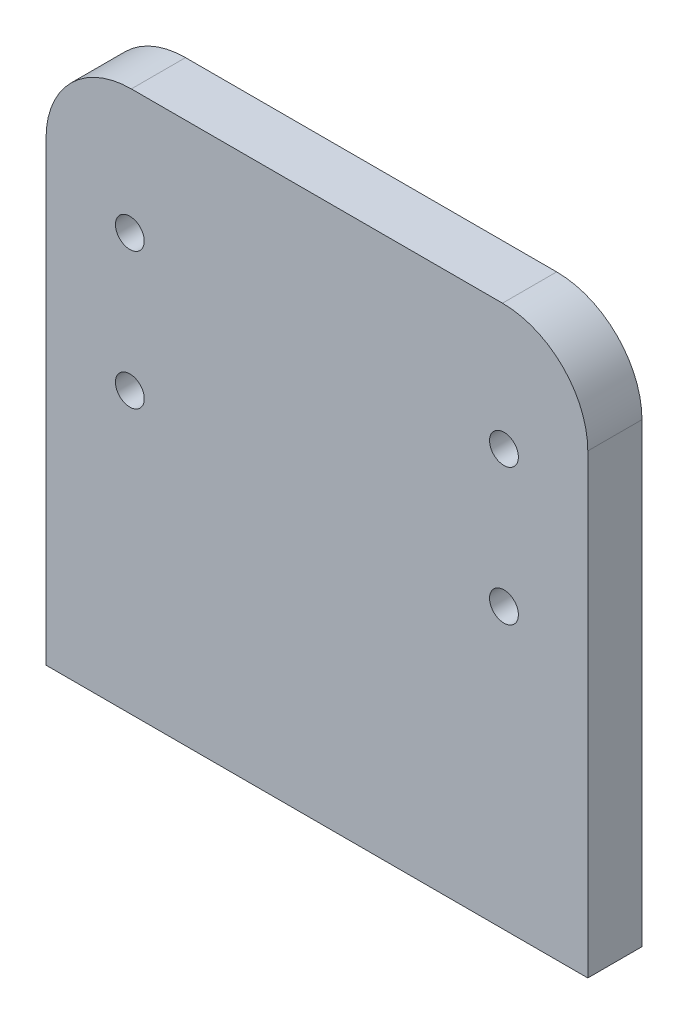
SolidWorks part; units mm, degrees
ref_plane "Alzado" through (0, 0, 0) normal (0, 0, 1) x (1, 0, 0)
ref_plane "Planta" through (0, 0, 0) normal (0, 1, 0) x (1, 0, 0)
ref_plane "Vista lateral" through (0, 0, 0) normal (1, 0, 0) x (0, 0, -1)
sketch "Croquis1" plane through (0, 0, 0) normal (0, 0, 1) x (1, 0, 0)
  line L1 (43.5, 63.5) -> (-43.5, 63.5)
  line L2 (63.5, 43.5) -> (63.5, -63.5)
  line L3 (63.5, -63.5) -> (-63.5, -63.5)
  line L4 (-63.5, 43.5) -> (-63.5, -63.5)
  line L5 (63.5, 63.5) -> (-63.5, -63.5) construction
  line L6 (63.5, -63.5) -> (-63.5, 63.5) construction
  arc A0 (43.5, 63.5) -> (63.5, 43.5) centre (43.5, 43.5) cw
  arc A1 (-43.5, 63.5) -> (-63.5, 43.5) centre (-43.5, 43.5) ccw
  point P0 (0, 0)
  dimension "D3" = 20
  dimension "D1" = 127
  dimension "D2" = 127
extrude "Saliente-Extruir1" add sketch "Croquis1" along normal mid plane 12.7
hole_wizard "Refrentado para tornillo con cabeza hueca de 1/41" positions "Croquis4" profile "Croquis5" counterbore size "1/4" standard "Ansi Inch" end condition through all
sketch "Croquis4" plane through (0, 0, -6.35) normal (0, 0, -1) x (-1, 0, 0)
  point P0 (43.85, 34.1)
  point P3 (43.85, 2.1)
  point P6 (-43.85, 2.1)
  point P9 (-43.85, 34.1)
sketch "Croquis5" plane through (-43.85, 34.1, -6.35) normal (1, 0, 0) x (0, 1, 0)
  line L0 (0, 0) -> (0, 12.7)
  line L1 (0, 12.7) -> (3.3782, 12.7)
  line L3 (3.3782, 12.7) -> (3.3782, 6.35)
  line L4 (3.3782, 6.35) -> (5.5562, 6.35)
  line L5 (5.5562, 6.35) -> (5.5562, 0)
  line L7 (5.5562, 0) -> (0, 0)
  line L11 (0, -6.35) -> (0, 107.95) construction
  dimension "Diámetro de taladro hasta el siguiente" = 6.7564
  dimension "Profundidad de taladro hasta el siguiente" = 12.7
  dimension "Diámetro de refrentado" = 11.1125
  dimension "Profundidad de refrentado" = 6.35
hole_wizard "M4 Clearance Hole1" positions "Sketch3" profile "Sketch4" hole size "M4" standard "DIN"
sketch "Sketch3" plane through (0, 0, 6.35) normal (0, 0, 1) x (1, 0, 0)
  point P0 (25, -26)
  point P2 (0, -26)
  point P4 (-25, -26)
  point P6 (-25, -56)
  point P8 (0, -56)
  point P10 (25, -56)
sketch "Sketch4" plane through (25, -26, 6.35) normal (1, 0, 0) x (0, -1, 0)
  line L0 (0, 0) -> (0, 12.7)
  line L1 (0, 12.7) -> (2.25, 12.7)
  line L2 (2.25, 12.7) -> (2.25, 0)
  line L5 (2.25, 0) -> (0, 0)
  line L11 (0, -6.35) -> (0, 107.95) construction
  dimension "Thru Hole Dia." = 4.5
  dimension "Thru Hole Depth" = 12.7
